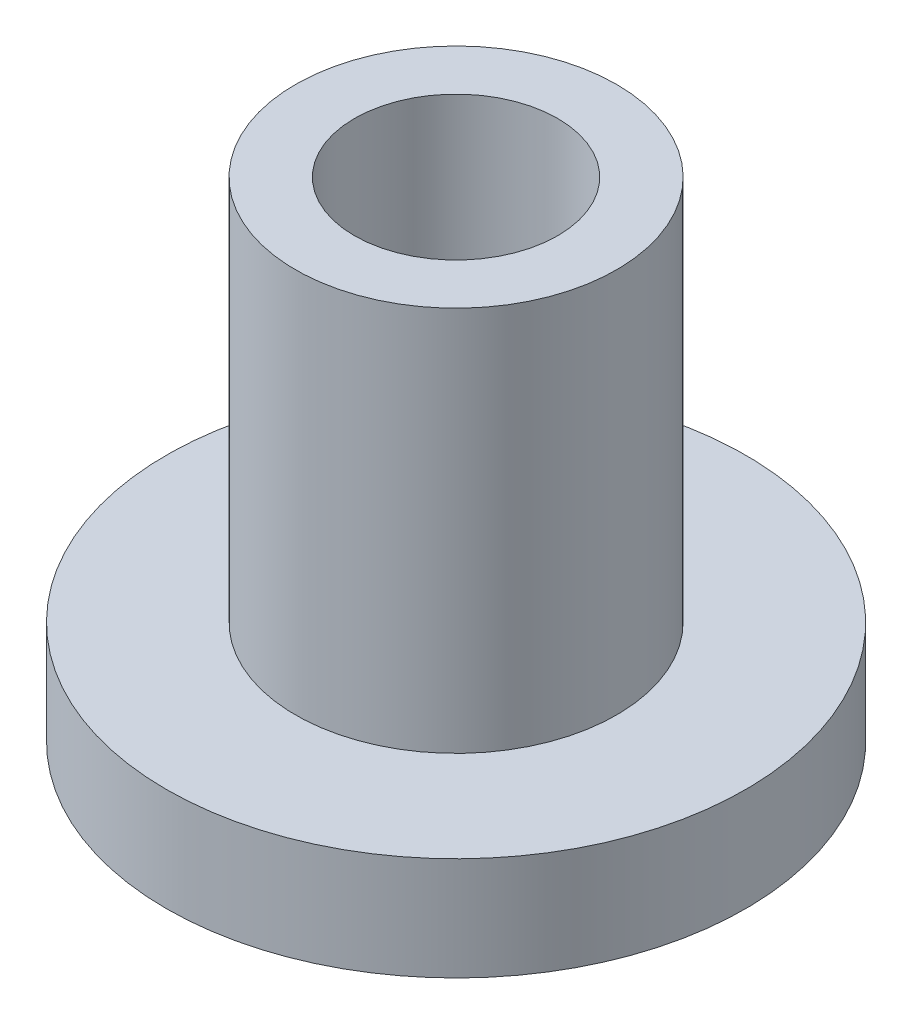
SolidWorks part; units mm, degrees
ref_plane "Front Plane" through (0, 0, 0) normal (0, 0, 1) x (1, 0, 0)
ref_plane "Top Plane" through (0, 0, 0) normal (0, 1, 0) x (1, 0, 0)
ref_plane "Right Plane" through (0, 0, 0) normal (1, 0, 0) x (0, 0, -1)
ref_plane "Plane1"
sketch "Sketch1" plane through (0, 5, 0) normal (0, 1, 0) x (1, 0, 0)
  circle A0 centre (0, 0) radius 7.9
  dimension "D1" = 15.8
extrude "Extrusion2" add sketch "Sketch1" along normal blind 19.05
sketch "Sketch2" plane through (0, 24.05, 0) normal (0, 1, 0) x (-1, 0, 0)
  circle A0 centre (0, 0) radius 5
  dimension "D1" = 10
extrude "Extrusion3" cut sketch "Sketch2" against normal up to next
ref_plane "Plane2"
sketch "Sketch3" plane through (0, 0, 0) normal (0, 1, 0) x (-1, 0, 0)
  circle A0 centre (0, 0) radius 14.25
  dimension "D1" = 28.5
extrude "Extrusion4" add sketch "Sketch3" along normal blind 5.08
sketch "Sketch4" plane through (0, 5.08, 0) normal (0, 1, 0) x (-1, 0, 0)
  circle A0 centre (0, 0) radius 5
extrude "Extrusion5" cut sketch "Sketch4" against normal up to next
